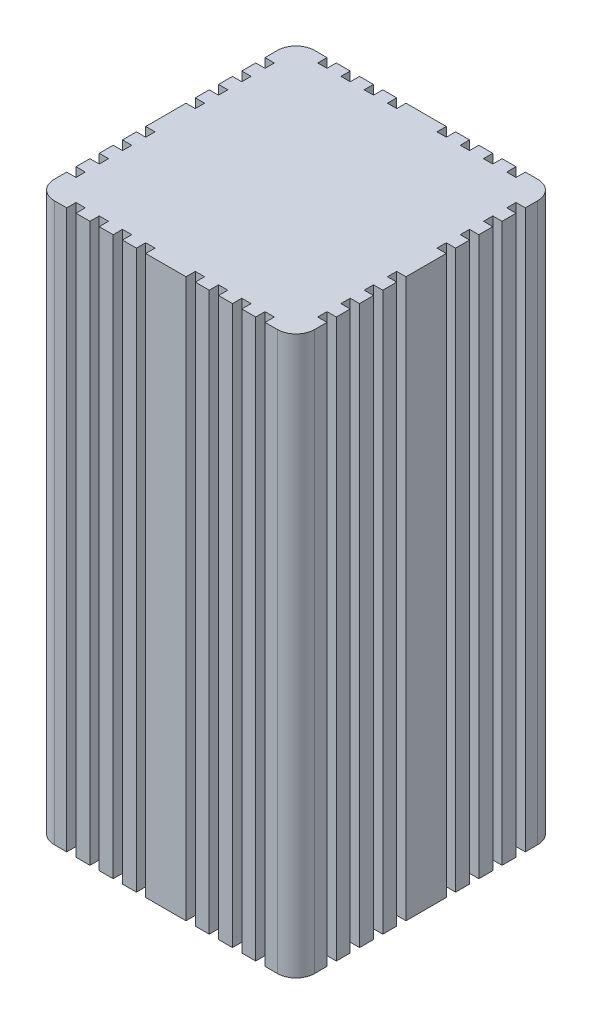
SolidWorks part; units mm, degrees
ref_plane "Plan de face" through (0, 0, 0) normal (0, 0, 1) x (1, 0, 0)
ref_plane "Plan de dessus" through (0, 0, 0) normal (0, 1, 0) x (1, 0, 0)
ref_plane "Plan de droite" through (0, 0, 0) normal (1, 0, 0) x (0, 0, -1)
sketch "Esquisse1" plane through (0, 0, 0) normal (0, 1, 0) x (1, 0, 0)
  line L0 (-19.9092, -17.4323) -> (-21.4092, -17.4323)
  line L1 (-21.4092, -17.4323) -> (-21.4092, -19.4323)
  line L2 (-18.4092, -22.4323) -> (-16.4092, -22.4323)
  line L3 (-16.4092, -22.4323) -> (-16.4092, -20.9323)
  line L4 (-16.4092, -20.9323) -> (-14.9092, -20.9323)
  line L5 (-14.9092, -20.9323) -> (-14.9092, -22.4323)
  line L6 (-14.9092, -22.4323) -> (-12.6592, -22.4323)
  line L7 (-12.6592, -22.4323) -> (-12.6592, -20.9323)
  line L8 (-12.6592, -20.9323) -> (-11.1592, -20.9323)
  line L9 (-11.1592, -20.9323) -> (-11.1592, -22.4323)
  line L10 (-11.1592, -22.4323) -> (-8.9092, -22.4323)
  line L11 (-8.9092, -22.4323) -> (-8.9092, -20.9323)
  line L12 (-8.9092, -20.9323) -> (-7.4092, -20.9323)
  line L13 (-7.4092, -20.9323) -> (-7.4092, -22.4323)
  line L14 (-7.4092, -22.4323) -> (-5.1592, -22.4323)
  line L15 (-5.1592, -22.4323) -> (-5.1592, -20.9323)
  line L16 (-5.1592, -20.9323) -> (-3.6592, -20.9323)
  line L17 (-3.6592, -20.9323) -> (-3.6592, -22.4323)
  line L18 (-3.6592, -22.4323) -> (2.8408, -22.4323)
  line L19 (2.8408, -22.4323) -> (2.8408, -20.9323)
  line L20 (2.8408, -20.9323) -> (4.3408, -20.9323)
  line L21 (4.3408, -20.9323) -> (4.3408, -22.4323)
  line L22 (4.3408, -22.4323) -> (6.5908, -22.4323)
  line L23 (6.5908, -22.4323) -> (6.5908, -20.9323)
  line L24 (6.5908, -20.9323) -> (8.0908, -20.9323)
  line L25 (8.0908, -20.9323) -> (8.0908, -22.4323)
  line L26 (8.0908, -22.4323) -> (10.3408, -22.4323)
  line L27 (10.3408, -22.4323) -> (10.3408, -20.9323)
  line L28 (10.3408, -20.9323) -> (11.8408, -20.9323)
  line L29 (11.8408, -20.9323) -> (11.8408, -22.4323)
  line L30 (11.8408, -22.4323) -> (14.0908, -22.4323)
  line L31 (14.0908, -22.4323) -> (14.0908, -20.9323)
  line L32 (14.0908, -20.9323) -> (15.5908, -20.9323)
  line L33 (15.5908, -20.9323) -> (15.5908, -22.4323)
  line L34 (15.5908, -22.4323) -> (17.5908, -22.4323)
  line L35 (20.5908, -19.4323) -> (20.5908, -17.4323)
  line L36 (20.5908, -17.4323) -> (19.0908, -17.4323)
  line L37 (19.0908, -17.4323) -> (19.0908, -15.9323)
  line L38 (19.0908, -15.9323) -> (20.5908, -15.9323)
  line L39 (20.5908, -15.9323) -> (20.5908, -13.6823)
  line L40 (20.5908, -13.6823) -> (19.0908, -13.6823)
  line L41 (19.0908, -13.6823) -> (19.0908, -12.1823)
  line L42 (19.0908, -12.1823) -> (20.5908, -12.1823)
  line L43 (20.5908, -12.1823) -> (20.5908, -9.9323)
  line L44 (20.5908, -9.9323) -> (19.0908, -9.9323)
  line L45 (19.0908, -9.9323) -> (19.0908, -8.4323)
  line L46 (19.0908, -8.4323) -> (20.5908, -8.4323)
  line L47 (20.5908, -8.4323) -> (20.5908, -6.1823)
  line L48 (20.5908, -6.1823) -> (19.0908, -6.1823)
  line L49 (19.0908, -6.1823) -> (19.0908, -4.6823)
  line L50 (19.0908, -4.6823) -> (20.5908, -4.6823)
  line L51 (20.5908, -4.6823) -> (20.5908, 1.8177)
  line L52 (20.5908, 1.8177) -> (19.0908, 1.8177)
  line L53 (19.0908, 1.8177) -> (19.0908, 3.3177)
  line L54 (19.0908, 3.3177) -> (20.5908, 3.3177)
  line L55 (20.5908, 3.3177) -> (20.5908, 5.5677)
  line L56 (20.5908, 5.5677) -> (19.0908, 5.5677)
  line L57 (19.0908, 5.5677) -> (19.0908, 7.0677)
  line L58 (19.0908, 7.0677) -> (20.5908, 7.0677)
  line L59 (20.5908, 7.0677) -> (20.5908, 9.3177)
  line L60 (20.5908, 9.3177) -> (19.0908, 9.3177)
  line L61 (19.0908, 9.3177) -> (19.0908, 10.8177)
  line L62 (19.0908, 10.8177) -> (20.5908, 10.8177)
  line L63 (20.5908, 10.8177) -> (20.5908, 13.0677)
  line L64 (20.5908, 13.0677) -> (19.0908, 13.0677)
  line L65 (19.0908, 13.0677) -> (19.0908, 14.5677)
  line L66 (19.0908, 14.5677) -> (20.5908, 14.5677)
  line L67 (20.5908, 14.5677) -> (20.5908, 16.5677)
  line L68 (17.5908, 19.5677) -> (15.5908, 19.5677)
  line L69 (15.5908, 19.5677) -> (15.5908, 18.0677)
  line L70 (15.5908, 18.0677) -> (14.0908, 18.0677)
  line L71 (14.0908, 18.0677) -> (14.0908, 19.5677)
  line L72 (14.0908, 19.5677) -> (11.8408, 19.5677)
  line L73 (11.8408, 19.5677) -> (11.8408, 18.0677)
  line L74 (11.8408, 18.0677) -> (10.3408, 18.0677)
  line L75 (10.3408, 18.0677) -> (10.3408, 19.5677)
  line L76 (10.3408, 19.5677) -> (8.0908, 19.5677)
  line L77 (8.0908, 19.5677) -> (8.0908, 18.0677)
  line L78 (8.0908, 18.0677) -> (6.5908, 18.0677)
  line L79 (6.5908, 18.0677) -> (6.5908, 19.5677)
  line L80 (6.5908, 19.5677) -> (4.3408, 19.5677)
  line L81 (4.3408, 19.5677) -> (4.3408, 18.0677)
  line L82 (4.3408, 18.0677) -> (2.8408, 18.0677)
  line L83 (2.8408, 18.0677) -> (2.8408, 19.5677)
  line L84 (2.8408, 19.5677) -> (-3.6592, 19.5677)
  line L85 (-3.6592, 19.5677) -> (-3.6592, 18.0677)
  line L86 (-3.6592, 18.0677) -> (-5.1592, 18.0677)
  line L87 (-5.1592, 18.0677) -> (-5.1592, 19.5677)
  line L88 (-5.1592, 19.5677) -> (-7.4092, 19.5677)
  line L89 (-7.4092, 19.5677) -> (-7.4092, 18.0677)
  line L90 (-7.4092, 18.0677) -> (-8.9092, 18.0677)
  line L91 (-8.9092, 18.0677) -> (-8.9092, 19.5677)
  line L92 (-8.9092, 19.5677) -> (-11.1592, 19.5677)
  line L93 (-11.1592, 19.5677) -> (-11.1592, 18.0677)
  line L94 (-11.1592, 18.0677) -> (-12.6592, 18.0677)
  line L95 (-12.6592, 18.0677) -> (-12.6592, 19.5677)
  line L96 (-12.6592, 19.5677) -> (-14.9092, 19.5677)
  line L97 (-14.9092, 19.5677) -> (-14.9092, 18.0677)
  line L98 (-14.9092, 18.0677) -> (-16.4092, 18.0677)
  line L99 (-16.4092, 18.0677) -> (-16.4092, 19.5677)
  line L100 (-16.4092, 19.5677) -> (-18.4092, 19.5677)
  line L101 (-21.4092, 16.5677) -> (-21.4092, 14.5677)
  line L102 (-21.4092, 14.5677) -> (-19.9092, 14.5677)
  line L103 (-19.9092, 14.5677) -> (-19.9092, 13.0677)
  line L104 (-19.9092, 13.0677) -> (-21.4092, 13.0677)
  line L105 (-21.4092, 13.0677) -> (-21.4092, 10.8177)
  line L106 (-21.4092, 10.8177) -> (-19.9092, 10.8177)
  line L107 (-19.9092, 10.8177) -> (-19.9092, 9.3177)
  line L108 (-19.9092, 9.3177) -> (-21.4092, 9.3177)
  line L109 (-21.4092, 9.3177) -> (-21.4092, 7.0677)
  line L110 (-21.4092, 7.0677) -> (-19.9092, 7.0677)
  line L111 (-19.9092, 7.0677) -> (-19.9092, 5.5677)
  line L112 (-19.9092, 5.5677) -> (-21.4092, 5.5677)
  line L113 (-21.4092, 5.5677) -> (-21.4092, 3.3177)
  line L114 (-21.4092, 3.3177) -> (-19.9092, 3.3177)
  line L115 (-19.9092, 3.3177) -> (-19.9092, 1.8177)
  line L116 (-19.9092, 1.8177) -> (-21.4092, 1.8177)
  line L117 (-21.4092, 1.8177) -> (-21.4092, -4.6823)
  line L118 (-21.4092, -4.6823) -> (-19.9092, -4.6823)
  line L119 (-19.9092, -4.6823) -> (-19.9092, -6.1823)
  line L120 (-19.9092, -6.1823) -> (-21.4092, -6.1823)
  line L121 (-21.4092, -6.1823) -> (-21.4092, -8.4323)
  line L122 (-21.4092, -8.4323) -> (-19.9092, -8.4323)
  line L123 (-19.9092, -8.4323) -> (-19.9092, -9.9323)
  line L124 (-19.9092, -9.9323) -> (-21.4092, -9.9323)
  line L125 (-21.4092, -9.9323) -> (-21.4092, -12.1823)
  line L126 (-21.4092, -12.1823) -> (-19.9092, -12.1823)
  line L127 (-19.9092, -12.1823) -> (-19.9092, -13.6823)
  line L128 (-19.9092, -13.6823) -> (-21.4092, -13.6823)
  line L129 (-21.4092, -13.6823) -> (-21.4092, -15.9323)
  line L130 (-21.4092, -15.9323) -> (-19.9092, -15.9323)
  line L131 (-19.9092, -15.9323) -> (-19.9092, -17.4323)
  arc A0 (-21.4092, -19.4323) -> (-18.4092, -22.4323) centre (-18.4092, -19.4323) ccw
  arc A1 (17.5908, -22.4323) -> (20.5908, -19.4323) centre (17.5908, -19.4323) ccw
  arc A2 (20.5908, 16.5677) -> (17.5908, 19.5677) centre (17.5908, 16.5677) ccw
  arc A3 (-18.4092, 19.5677) -> (-21.4092, 16.5677) centre (-18.4092, 16.5677) ccw
extrude "Boss.-Extru.1" add sketch "Esquisse1" along normal blind 90
sketch "Esquisse2" plane through (0, 0, 0) normal (0, -1, 0) x (1, 0, 0)
  circle A0 centre (0, 0) radius 7
  circle A1 centre (0, 0) radius 4
  dimension "D1" = 14
  dimension "D2" = 3
extrude "Boss.-Extru.2" add sketch "Esquisse2" along normal blind 6
fillet "Congé1" radius 1 1 edges at (0, -6, -7)
